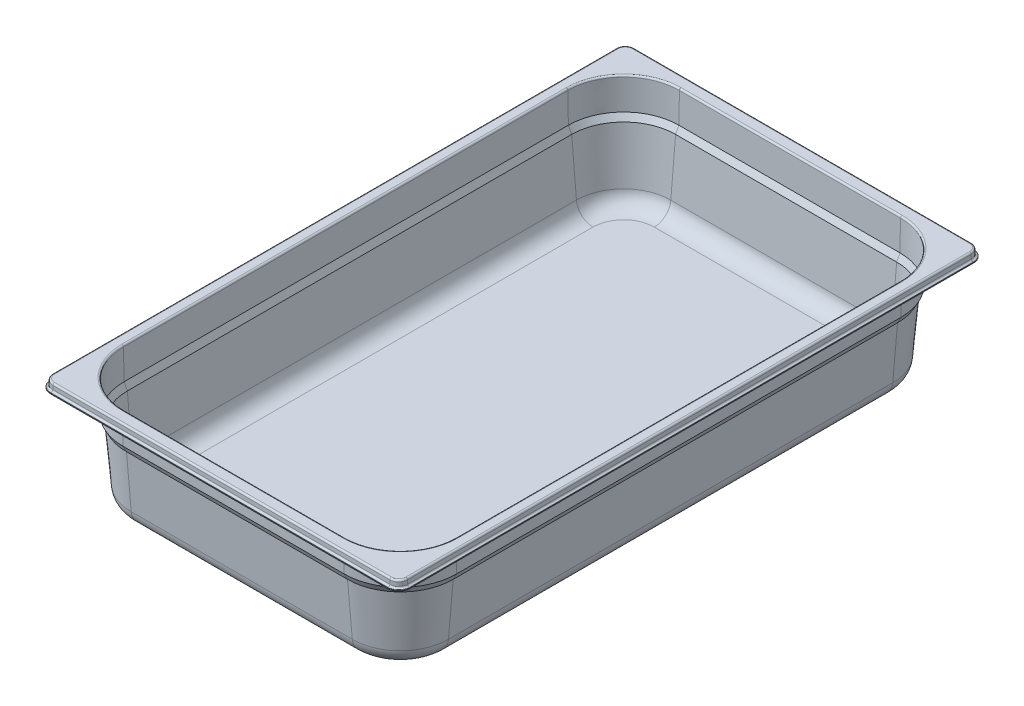
SolidWorks part; units mm, degrees
ref_plane "Front Plane" through (0, 0, 0) normal (0, 0, 1) x (1, 0, 0)
ref_plane "Top Plane" through (0, 0, 0) normal (0, 1, 0) x (1, 0, 0)
ref_plane "Right Plane" through (0, 0, 0) normal (1, 0, 0) x (0, 0, -1)
sketch "Sketch1" plane through (0, 0, 0) normal (0, 1, 0) x (1, 0, 0)
  line L1 (10, 0) -> (315, 0)
  line L2 (0, 10) -> (0, 520)
  line L3 (10, 530) -> (315, 530)
  line L4 (325, 10) -> (325, 520)
  arc A0 (315, 0) -> (325, 10) centre (315, 10) ccw
  arc A1 (10, 0) -> (0, 10) centre (10, 10) cw
  arc A2 (315, 530) -> (325, 520) centre (315, 520) cw
  arc A3 (0, 520) -> (10, 530) centre (10, 520) cw
  point P7 (325, 0)
  point P10 (0, 0)
  point P15 (0, 530)
  dimension "D3" = 10
  dimension "D1" = 325
  dimension "D2" = 530
ref_plane "Plane1" through (0, 0, -10) normal (0, 0, 1) x (1, 0, 0)
sketch "Sketch2" plane through (0, 0, -10) normal (0, 0, 1) x (1, 0, 0)
  line L0 (0, -6.5) -> (0.5, -6.5)
  line L1 (2, -5) -> (2, -1.5)
  line L2 (10, 0) -> (0, 0) construction
  line L3 (3.5, 0) -> (10.5278, 0)
  line L4 (12.0276, -1.4738) -> (12.4993, -28.5)
  line L5 (12.4993, -28.5) -> (15.4993, -34.2)
  line L6 (15.4993, -34.2) -> (19.8131, -83.5073)
  line L7 (34.7561, -97.2) -> (44.7561, -97.2)
  line L9 (10, 0) -> (315, 0) construction
  line L10 (0, -7.3) -> (0.5, -7.3)
  line L11 (2.8, -5) -> (2.8, -1.5)
  line L12 (3.5, -0.8) -> (10.5278, -0.8)
  line L13 (11.2277, -1.4878) -> (11.7027, -28.7042)
  line L14 (11.7027, -28.7042) -> (14.7164, -34.4301)
  line L15 (14.7164, -34.4301) -> (19.0162, -83.5771)
  line L16 (34.7561, -98) -> (44.7561, -98)
  line L17 (0, -6.5) -> (0, -7.3)
  line L18 (44.7561, -97.2) -> (44.7561, -98)
  arc A0 (19.8131, -83.5073) -> (34.7561, -97.2) centre (34.7561, -82.2) ccw
  arc A1 (10.5278, 0) -> (12.0276, -1.4738) centre (10.5278, -1.5) cw
  arc A2 (0.5, -6.5) -> (2, -5) centre (0.5, -5) ccw
  arc A3 (2, -1.5) -> (3.5, 0) centre (3.5, -1.5) cw
  arc A4 (0.5, -7.3) -> (2.8, -5) centre (0.5, -5) ccw
  arc A5 (2.8, -1.5) -> (3.5, -0.8) centre (3.5, -1.5) cw
  arc A6 (10.5278, -0.8) -> (11.2277, -1.4878) centre (10.5278, -1.5) cw
  arc A7 (19.0162, -83.5771) -> (34.7561, -98) centre (34.7561, -82.2) ccw
  point P24 (12.0018, 0)
  point P29 (2, 0)
  dimension "D1" = 15
  dimension "D12" = 1.5
  dimension "D2" = 10
  dimension "D3" = 6.5
  dimension "D4" = 12
  dimension "D5" = 2
  dimension "D6" = 95
  dimension "D7" = 91
  dimension "D8" = 28.5
  dimension "D9" = 34.2
  dimension "D10" = 3
  dimension "D11" = 97.2
  dimension "D13" = 0.8
sketch "Sketch7" plane through (0, 0, -10) normal (0, 0, 1) x (1, 0, 0)
  line L0 (2, -5) -> (2, -1.5) construction
  line L1 (0, -6.5) -> (0.5, -6.5) construction
  line L2 (0, -6.5) -> (0, -7.3) construction
  line L3 (0, -7.3) -> (0.5, -7.3) construction
  line L4 (2.8, -5) -> (2.8, -1.5) construction
  line L5 (2, -5) -> (2, -1.5)
  line L6 (0, -6.5) -> (0.5, -6.5)
  line L7 (0, -6.5) -> (0, -7.3)
  line L8 (0, -7.3) -> (0.5, -7.3)
  line L9 (2.8, -5) -> (2.8, -1.5)
  line L10 (3.5, 0) -> (3.5, -0.8)
  arc A0 (3.5, -0.8) -> (2.8, -1.5) centre (3.5, -1.5) ccw construction
  arc A1 (3.5, 0) -> (2, -1.5) centre (3.5, -1.5) ccw construction
  arc A2 (0.5, -6.5) -> (2, -5) centre (0.5, -5) ccw construction
  arc A3 (0.5, -7.3) -> (2.8, -5) centre (0.5, -5) ccw construction
  arc A4 (3.5, -0.8) -> (2.8, -1.5) centre (3.5, -1.5) ccw
  arc A5 (3.5, 0) -> (2, -1.5) centre (3.5, -1.5) ccw
  arc A6 (0.5, -6.5) -> (2, -5) centre (0.5, -5) ccw
  arc A7 (0.5, -7.3) -> (2.8, -5) centre (0.5, -5) ccw
sweep "Sweep9" add profiles "Sketch7" path "Sketch1"
sketch "Sketch9" plane through (0, 0, 0) normal (0, 1, 0) x (1, 0, 0)
  line L0 (62.5, 516) -> (262.5, 516)
  line L1 (312.5, 466) -> (312.5, 64)
  line L2 (262.5, 14) -> (62.5, 14)
  line L3 (12.5, 64) -> (12.5, 466)
  line L4 (27.1447, 28.6447) -> (5.4038, 5.4038) construction
  line L5 (297.8553, 501.3553) -> (319.5962, 524.5962) construction
  line L6 (297.8553, 28.6447) -> (319.5962, 5.4038) construction
  arc A0 (262.5, 516) -> (312.5, 466) centre (262.5, 466) cw
  arc A1 (312.5, 64) -> (262.5, 14) centre (262.5, 64) cw
  arc A2 (62.5, 14) -> (12.5, 64) centre (62.5, 64) cw
  arc A3 (12.5, 466) -> (62.5, 516) centre (62.5, 466) cw
  arc A4 (3.5, 10) -> (10, 3.5) centre (10, 10) ccw construction
  arc A8 (315, 3.5) -> (321.5, 10) centre (315, 10) ccw construction
  arc A9 (321.5, 520) -> (315, 526.5) centre (315, 520) ccw construction
  dimension "D1" = 50
  dimension "D2" = 300
  dimension "D3" = 502
ref_plane "Plane2" through (0, 0, -64) normal (0, 0, 1) x (1, 0, 0)
sketch "Sketch10" plane through (0, 0, -64) normal (0, 0, 1) x (1, 0, 0)
  line L0 (10.5278, 0) -> (10.5278, -0.8)
  line L16 (2.8, -5) -> (2.8, -1.5)
  line L17 (3.5, -0.8) -> (10.5278, -0.8)
  line L18 (11.2277, -1.4878) -> (11.7027, -28.7042)
  line L19 (11.7027, -28.7042) -> (14.7164, -34.4301)
  line L20 (14.7164, -34.4301) -> (19.0162, -83.5771)
  line L21 (34.7561, -98) -> (44.7561, -98)
  line L22 (44.7561, -98) -> (44.7561, -97.2)
  line L23 (44.7561, -97.2) -> (34.7561, -97.2)
  line L24 (19.8131, -83.5073) -> (15.4993, -34.2)
  line L25 (15.4993, -34.2) -> (12.4993, -28.5)
  line L26 (12.4993, -28.5) -> (12.0276, -1.4738)
  line L27 (10.5278, 0) -> (3.5, 0)
  line L28 (2, -1.5) -> (2, -5)
  line L29 (0.5, -6.5) -> (0, -6.5)
  line L30 (0, -6.5) -> (0, -7.3)
  line L31 (0, -7.3) -> (0.5, -7.3)
  line L34 (11.2277, -1.4878) -> (11.7027, -28.7042)
  line L35 (11.7027, -28.7042) -> (14.7164, -34.4301)
  line L36 (14.7164, -34.4301) -> (19.0162, -83.5771)
  line L37 (34.7561, -98) -> (44.7561, -98)
  line L38 (44.7561, -98) -> (44.7561, -97.2)
  line L39 (44.7561, -97.2) -> (34.7561, -97.2)
  line L40 (19.8131, -83.5073) -> (15.4993, -34.2)
  line L41 (15.4993, -34.2) -> (12.4993, -28.5)
  line L42 (12.4993, -28.5) -> (12.0276, -1.4738)
  arc A8 (3.5, -0.8) -> (2.8, -1.5) centre (3.5, -1.5) ccw
  arc A9 (11.2277, -1.4878) -> (10.5278, -0.8) centre (10.5278, -1.5) ccw
  arc A10 (19.0162, -83.5771) -> (34.7561, -98) centre (34.7561, -82.2) ccw
  arc A11 (19.8131, -83.5073) -> (34.7561, -97.2) centre (34.7561, -82.2) ccw
  arc A12 (12.0276, -1.4738) -> (10.5278, 0) centre (10.5278, -1.5) ccw
  arc A13 (3.5, 0) -> (2, -1.5) centre (3.5, -1.5) ccw
  arc A14 (0.5, -6.5) -> (2, -5) centre (0.5, -5) ccw
  arc A15 (0.5, -7.3) -> (2.8, -5) centre (0.5, -5) ccw
  arc A17 (11.2277, -1.4878) -> (10.5278, -0.8) centre (10.5278, -1.5) ccw
  arc A18 (19.0162, -83.5771) -> (34.7561, -98) centre (34.7561, -82.2) ccw
  arc A19 (19.8131, -83.5073) -> (34.7561, -97.2) centre (34.7561, -82.2) ccw
  arc A20 (12.0276, -1.4738) -> (10.5278, 0) centre (10.5278, -1.5) ccw
  dimension "D1" = 0
sweep "Sweep10" add profiles "Sketch10" path "Sketch9"
sketch "Sketch11" plane through (0, 0, 0) normal (0, 1, 0) x (1, 0, 0)
  line L0 (321.5, 520) -> (321.5, 10) construction
  line L1 (315, 3.5) -> (10, 3.5) construction
  line L2 (3.5, 10) -> (3.5, 520) construction
  line L3 (10, 526.5) -> (315, 526.5) construction
  line L4 (321.5, 520) -> (321.5, 10)
  line L5 (315, 3.5) -> (10, 3.5)
  line L6 (3.5, 10) -> (3.5, 520)
  line L7 (10, 526.5) -> (315, 526.5)
  line L8 (62.5, 517.9722) -> (262.5, 517.9722) construction
  line L9 (314.4722, 466) -> (314.4722, 64) construction
  line L10 (10.5278, 64) -> (10.5278, 466) construction
  line L11 (10.5278, 64) -> (10.5278, 466)
  line L12 (314.4722, 466) -> (314.4722, 64)
  line L13 (62.5, 517.9722) -> (262.5, 517.9722)
  line L14 (262.5, 12.0278) -> (62.5, 12.0278) construction
  line L15 (262.5, 12.0278) -> (62.5, 12.0278)
  arc A0 (321.5, 520) -> (315, 526.5) centre (315, 520) ccw construction
  arc A1 (315, 3.5) -> (321.5, 10) centre (315, 10) ccw construction
  arc A2 (3.5, 10) -> (10, 3.5) centre (10, 10) ccw construction
  arc A3 (10, 526.5) -> (3.5, 520) centre (10, 520) ccw construction
  arc A4 (321.5, 520) -> (315, 526.5) centre (315, 520) ccw
  arc A5 (315, 3.5) -> (321.5, 10) centre (315, 10) ccw
  arc A6 (3.5, 10) -> (10, 3.5) centre (10, 10) ccw
  arc A7 (10, 526.5) -> (3.5, 520) centre (10, 520) ccw
  arc A8 (62.5, 517.9722) -> (10.5278, 466) centre (62.5, 466) ccw construction
  arc A9 (314.4722, 466) -> (262.5, 517.9722) centre (262.5, 466) ccw construction
  arc A10 (10.5278, 64) -> (62.5, 12.0278) centre (62.5, 64) ccw construction
  arc A11 (262.5, 12.0278) -> (314.4722, 64) centre (262.5, 64) ccw construction
  arc A12 (10.5278, 64) -> (62.5, 12.0278) centre (62.5, 64) ccw
  arc A13 (262.5, 12.0278) -> (314.4722, 64) centre (262.5, 64) ccw
  arc A14 (314.4722, 466) -> (262.5, 517.9722) centre (262.5, 466) ccw
  arc A15 (62.5, 517.9722) -> (10.5278, 466) centre (62.5, 466) ccw
extrude "Boss-Extrude2" add sketch "Sketch11" against normal blind 0.8
ref_plane "Plane3" through (0, -98, 0) normal (0, -1, 0) x (-1, 0, 0)
sketch "Sketch12" plane through (0, -98, 0) normal (0, -1, 0) x (-1, 0, 0)
  line L0 (-62.5, 483.7439) -> (-262.5, 483.7439) construction
  line L1 (-62.5, 483.7439) -> (-262.5, 483.7439)
  line L2 (-44.7561, 64) -> (-44.7561, 466) construction
  line L3 (-44.7561, 64) -> (-44.7561, 466)
  line L4 (-262.5, 46.2561) -> (-62.5, 46.2561) construction
  line L5 (-262.5, 46.2561) -> (-62.5, 46.2561)
  line L6 (-280.2439, 466) -> (-280.2439, 64) construction
  line L7 (-280.2439, 466) -> (-280.2439, 64)
  arc A0 (-262.5, 483.7439) -> (-280.2439, 466) centre (-262.5, 466) ccw construction
  arc A1 (-262.5, 483.7439) -> (-280.2439, 466) centre (-262.5, 466) ccw
  arc A2 (-44.7561, 466) -> (-62.5, 483.7439) centre (-62.5, 466) ccw construction
  arc A3 (-44.7561, 466) -> (-62.5, 483.7439) centre (-62.5, 466) ccw
  arc A4 (-62.5, 46.2561) -> (-44.7561, 64) centre (-62.5, 64) ccw construction
  arc A5 (-62.5, 46.2561) -> (-44.7561, 64) centre (-62.5, 64) ccw
  arc A6 (-280.2439, 64) -> (-262.5, 46.2561) centre (-262.5, 64) ccw construction
  arc A7 (-280.2439, 64) -> (-262.5, 46.2561) centre (-262.5, 64) ccw
extrude "Boss-Extrude3" add sketch "Sketch12" against normal blind 0.8
